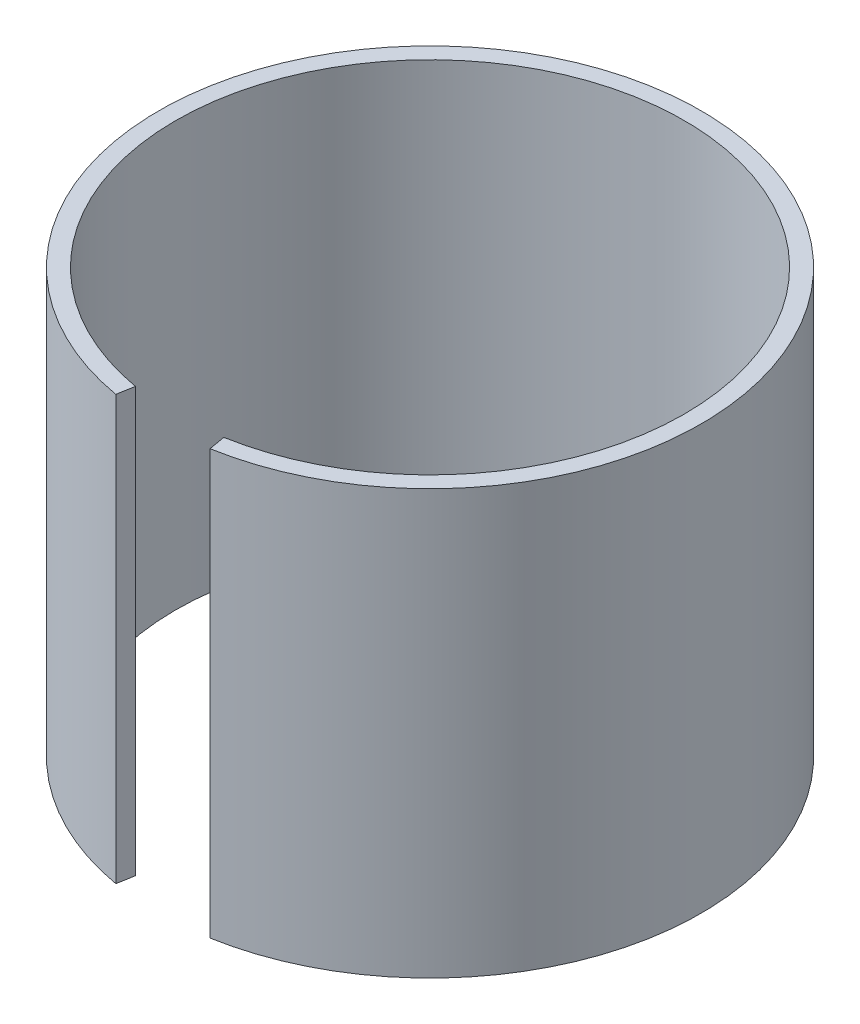
SolidWorks part; units mm, degrees
ref_plane "Front" through (0, 0, 0) normal (0, 0, 1) x (1, 0, 0)
ref_plane "Top" through (0, 0, 0) normal (0, 1, 0) x (1, 0, 0)
ref_plane "Right" through (0, 0, 0) normal (1, 0, 0) x (0, 0, -1)
other "Configuration Table"
sketch "Sketch1" plane through (0, 0, 0) normal (0, 1, 0) x (1, 0, 0)
  line L0 (0, 37.8702) -> (0, 30) construction
  line L1 (5.2094, -29.5442) -> (5.5567, -31.5138)
  line L2 (-5.2094, -29.5442) -> (-5.5567, -31.5138)
  arc A0 (5.2094, -29.5442) -> (-5.2094, -29.5442) centre (0, 0) ccw
  arc A1 (5.5567, -31.5138) -> (-5.5567, -31.5138) centre (0, 0) ccw
  dimension "D1" = 2
  dimension "D2" = 60
extrude "Extrude1" add sketch "Sketch1" along normal blind 50
